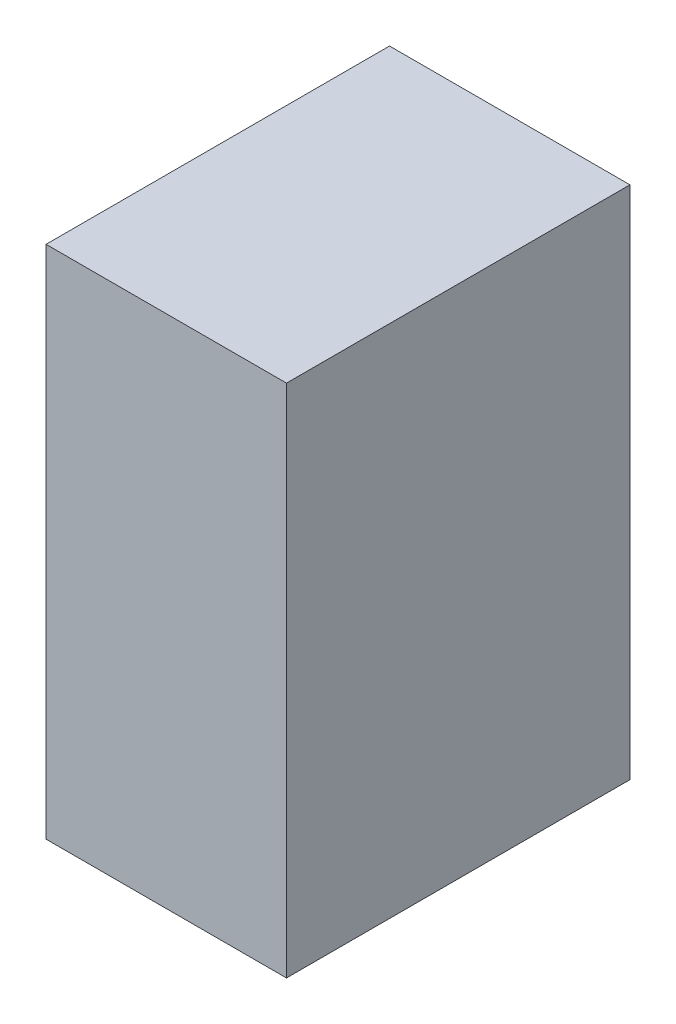
SolidWorks part; units mm, degrees
ref_plane "Front Plane" through (0, 0, 0) normal (0, 0, 1) x (1, 0, 0)
ref_plane "Top Plane" through (0, 0, 0) normal (0, 1, 0) x (1, 0, 0)
ref_plane "Right Plane" through (0, 0, 0) normal (1, 0, 0) x (0, 0, -1)
other "Bounding Box"
ref_plane "Default Plane" through (-8.9266, -12.7485, 0) normal (-0.1736, 0.9848, 0) x (0.9848, 0.1736, 0)
sketch "Sketch1" plane through (0, 0, 0) normal (0, 1, 0) x (1, 0, 0)
  line L1 (-17.78, 25.4) -> (17.78, 25.4)
  line L2 (-17.78, 25.4) -> (-17.78, -25.4)
  line L3 (-17.78, -25.4) -> (17.78, -25.4)
  line L4 (17.78, 25.4) -> (17.78, -25.4)
  line L5 (-17.78, 25.4) -> (17.78, -25.4) construction
  line L6 (-17.78, -25.4) -> (17.78, 25.4) construction
  point P0 (0, 0)
  dimension "D1" = 35.56
  dimension "D2" = 50.8
extrude "Boss-Extrude1" add sketch "Sketch1" along normal mid plane 76.2
